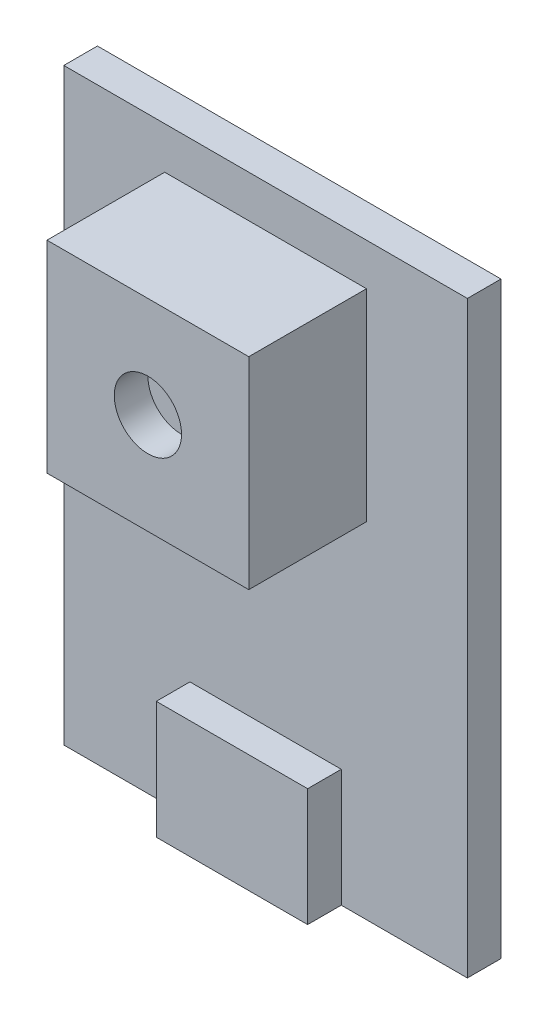
SolidWorks part; units mm, degrees
ref_plane "정면" through (0, 0, 0) normal (0, 0, 1) x (1, 0, 0)
ref_plane "윗면" through (0, 0, 0) normal (0, 1, 0) x (1, 0, 0)
ref_plane "우측면" through (0, 0, 0) normal (1, 0, 0) x (0, 0, -1)
sketch "스케치1" plane through (0, 0, 0) normal (0, 0, 1) x (1, 0, 0)
  line L5 (-6, 6) -> (6, 6)
  line L6 (-6, 6) -> (-6, -6)
  line L7 (-6, -6) -> (6, -6)
  line L8 (6, 6) -> (6, -6)
  line L9 (-6, 6) -> (6, -6) construction
  line L10 (-6, -6) -> (6, 6) construction
  point P0 (0, 0)
  dimension "D1" = 12
  dimension "D2" = 12
extrude "보스-돌출1" add sketch "스케치1" along normal blind 7
sketch "스케치2" plane through (0, 0, 0) normal (0, 0, -1) x (-1, 0, 0)
  line L1 (-12, -26.5) -> (12, -26.5)
  line L2 (-12, -26.5) -> (-12, 8.5)
  line L3 (-12, 8.5) -> (12, 8.5)
  line L4 (12, -26.5) -> (12, 8.5)
  line L5 (-12, -26.5) -> (12, 8.5) construction
  line L6 (-12, 8.5) -> (12, -26.5) construction
  point P0 (0, -9)
  dimension "D1" = 35
  dimension "D2" = 24
  dimension "D3" = 9
extrude "보스-돌출2" add sketch "스케치2" along normal blind 2
sketch "스케치3" plane through (0, 0, 0) normal (0, 0, 1) x (1, 0, 0)
  line L0 (12, -26.5) -> (-12, -26.5) construction
  line L1 (-4.5, -26.5) -> (4.5, -26.5)
  line L2 (-4.5, -26.5) -> (-4.5, -19.5)
  line L3 (-4.5, -19.5) -> (4.5, -19.5)
  line L4 (4.5, -26.5) -> (4.5, -19.5)
  point P6 (0, -19.5)
  dimension "D1" = 9
  dimension "D2" = 7
extrude "보스-돌출3" add sketch "스케치3" along normal blind 2
sketch "스케치4" plane through (0, 0, 7) normal (0, 0, 1) x (1, 0, 0)
  circle A0 centre (0, 0) radius 2
  dimension "D1" = 4
extrude "컷-돌출1" cut sketch "스케치4" against normal blind 2
